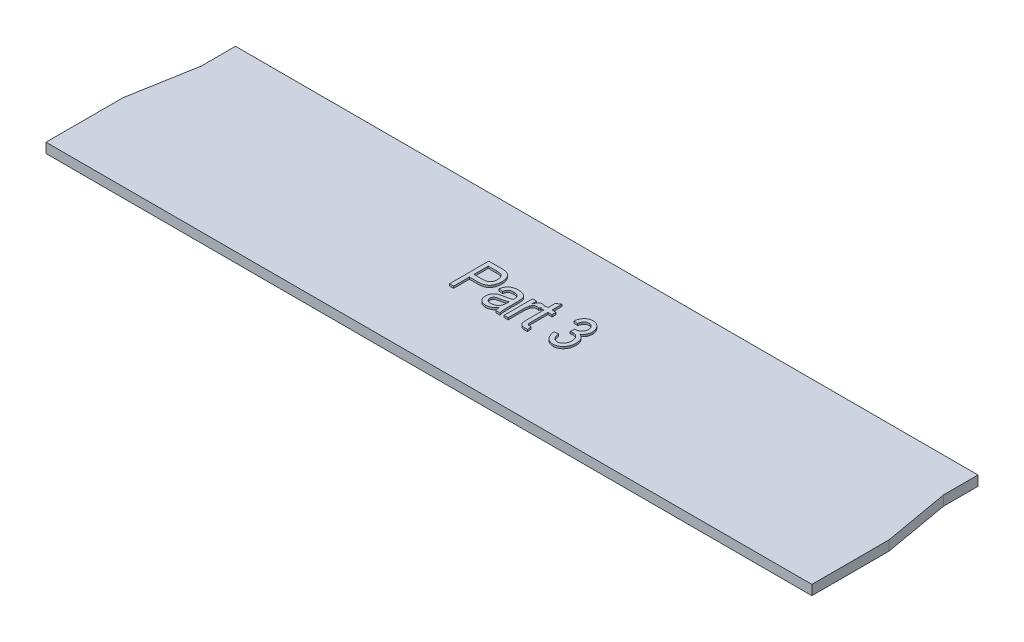
SolidWorks part; units mm, degrees
ref_plane "前视基准面" through (0, 0, 0) normal (0, 0, 1) x (1, 0, 0)
ref_plane "上视基准面" through (0, 0, 0) normal (0, 1, 0) x (1, 0, 0)
ref_plane "右视基准面" through (0, 0, 0) normal (1, 0, 0) x (0, 0, -1)
other "Configuration Table"
sketch "草图1" plane through (0, 0, 0) normal (0, 1, 0) x (1, 0, 0)
  line L0 (0, 0) -> (80, 0) construction
  line L1 (80, 0) -> (80, 8.9456) construction
  line L2 (80, 8.9456) -> (78.8091, 15.6994) construction
  line L3 (78.8091, 15.6994) -> (1.1909, 15.6994) construction
  line L4 (1.1909, 15.6994) -> (0, 8.9456) construction
  line L5 (0, 8.9456) -> (0, 0) construction
  line L6 (1.1909, 15.6994) -> (1.1909, 20.1093) construction
  line L7 (1.1909, 20.1093) -> (78.8091, 20.1093) construction
  line L8 (78.8091, 20.1093) -> (78.8091, 15.6994) construction
  line L9 (2.1909, 19.1093) -> (77.8091, 19.1093)
  line L10 (77.8091, 19.1093) -> (77.8091, 15.6119)
  line L11 (79, 8.8581) -> (77.8091, 15.6119)
  line L12 (79, 1) -> (79, 8.8581)
  line L13 (1, 1) -> (79, 1)
  line L14 (1, 8.8581) -> (1, 1)
  line L15 (2.1909, 15.6119) -> (1, 8.8581)
  line L16 (2.1909, 15.6119) -> (2.1909, 19.1093)
  dimension "D1" = 80
  dimension "D2" = 8.9456
  dimension "D3" = 6.8579
  dimension "D4" = 8.9456
  dimension "D5" = 6.8579
  dimension "D6" = 77.6183
  dimension "D7" = 4.4099
  dimension "D8" = 1
extrude "凸台-拉伸1" add sketch "草图1" along normal blind 1
sketch "草图2" plane through (0, 1, 0) normal (0, 1, 0) x (1, 0, 0)
  line L0 (1, 8.8581) -> (79, 8.8581) construction
  text T0 "Part 3" font "Arial Narrow" height 4
extrude "凸台-拉伸2" add sketch "草图2" along normal blind 0.2
